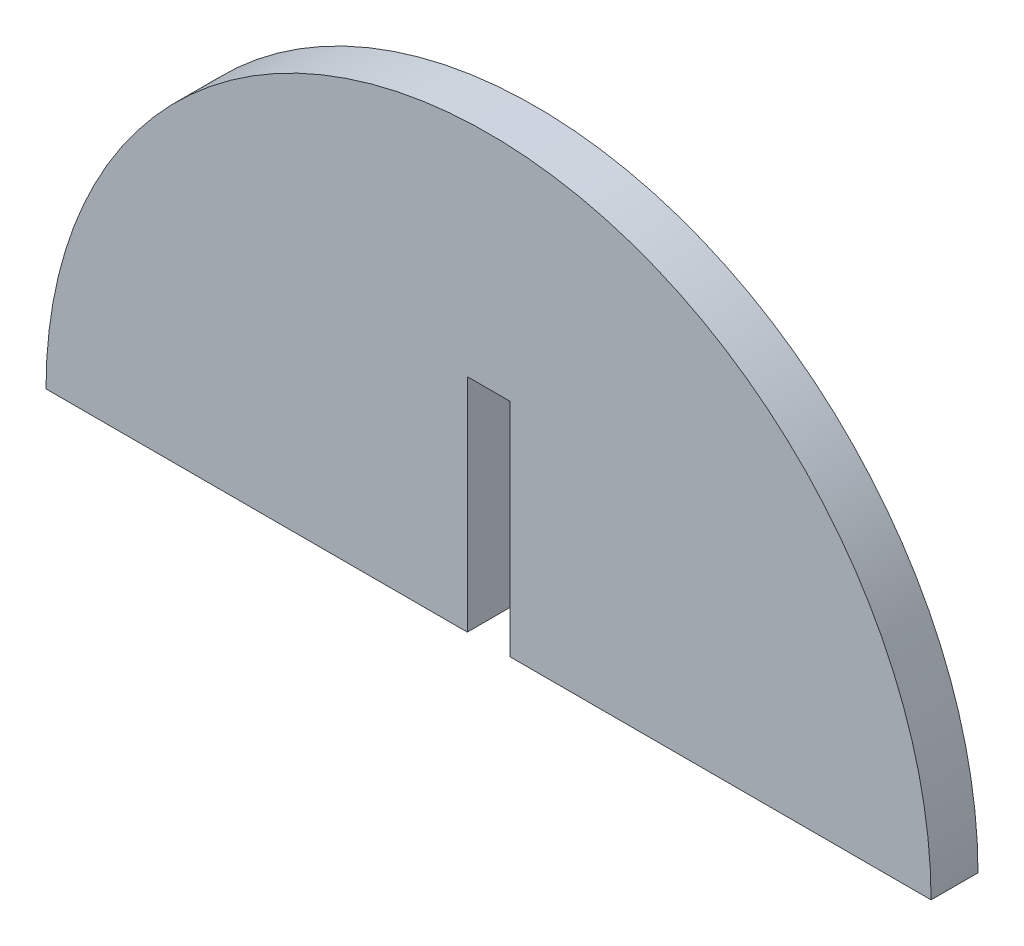
SolidWorks part; units mm, degrees
ref_plane "Front Plane" through (0, 0, 0) normal (0, 0, 1) x (1, 0, 0)
ref_plane "Top Plane" through (0, 0, 0) normal (0, 1, 0) x (1, 0, 0)
ref_plane "Right Plane" through (0, 0, 0) normal (1, 0, 0) x (0, 0, -1)
sketch "Sketch1" plane through (0, 0, 0) normal (0, 0, 1) x (1, 0, 0)
  line L0 (-25.4, 0) -> (-1.2192, 0)
  line L1 (-1.2192, 0) -> (-1.2192, 12.7)
  line L2 (-1.2192, 12.7) -> (1.2192, 12.7)
  line L3 (1.2192, 12.7) -> (1.2192, 0)
  line L4 (1.2192, 0) -> (25.4, 0)
  arc A0 (-25.4, 0) -> (25.4, 0) centre (0, 0) cw
  dimension "D1" = 25.4
  dimension "D2" = 2.4384
  dimension "D3" = 12.7
extrude "Boss-Extrude1" add sketch "Sketch1" along normal blind 2.6924
equation "\"T\"=0.106"
equation "\"D2@Sketch1\"=\"T\"-0.010"
equation "\"D1@Boss-Extrude1\"=\"T\""
